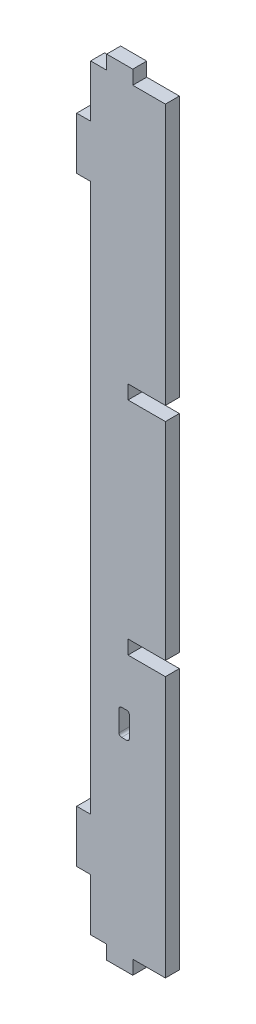
SolidWorks part; units mm, degrees
ref_plane "Front Plane" through (0, 0, 0) normal (0, 0, 1) x (1, 0, 0)
ref_plane "Top Plane" through (0, 0, 0) normal (0, 1, 0) x (1, 0, 0)
ref_plane "Right Plane" through (0, 0, 0) normal (1, 0, 0) x (0, 0, -1)
sketch "Model" plane through (0, 0, 0) normal (0, 0, 1) x (1, 0, 0)
  line L0 (20.1976, 77.8114) -> (20.1976, 85.8114)
  line L1 (19.1976, 86.8114) -> (17.1976, 86.8114)
  line L2 (16.1976, 85.8114) -> (16.1976, 77.8114)
  line L3 (17.1976, 76.8114) -> (19.1976, 76.8114)
  line L4 (0, 25.35) -> (5.35, 25.35)
  line L5 (0, 45.35) -> (0, 25.35)
  line L6 (5.35, 45.35) -> (0, 45.35)
  line L7 (5.35, 255.35) -> (5.35, 45.35)
  line L8 (0, 255.35) -> (5.35, 255.35)
  line L9 (0, 275.35) -> (0, 255.35)
  line L10 (5.35, 275.35) -> (0, 275.35)
  line L11 (5.35, 295.35) -> (5.35, 275.35)
  line L12 (11.5, 295.35) -> (5.35, 295.35)
  line L13 (11.5, 300.7) -> (11.5, 295.35)
  line L14 (21.5, 300.7) -> (11.5, 300.7)
  line L15 (21.5, 295.35) -> (21.5, 300.7)
  line L16 (34, 295.35) -> (21.5, 295.35)
  line L17 (34, 195.35) -> (34, 295.35)
  line L18 (19.675, 195.35) -> (34, 195.35)
  line L19 (19.675, 190) -> (19.675, 195.35)
  line L20 (34, 190) -> (19.675, 190)
  line L21 (34, 110.7) -> (34, 190)
  line L22 (19.675, 110.7) -> (34, 110.7)
  line L23 (19.675, 105.35) -> (19.675, 110.7)
  line L24 (34, 105.35) -> (19.675, 105.35)
  line L25 (34, 5.35) -> (34, 105.35)
  line L26 (21.5, 5.35) -> (34, 5.35)
  line L27 (21.5, 0) -> (21.5, 5.35)
  line L28 (11.5, 0) -> (21.5, 0)
  line L29 (11.5, 5.35) -> (11.5, 0)
  line L30 (5.35, 5.35) -> (11.5, 5.35)
  line L31 (5.35, 25.35) -> (5.35, 5.35)
  arc A0 (19.1976, 76.8114) -> (20.1976, 77.8114) centre (19.1976, 77.8114) ccw
  arc A1 (20.1976, 85.8114) -> (19.1976, 86.8114) centre (19.1976, 85.8114) ccw
  arc A2 (17.1976, 86.8114) -> (16.1976, 85.8114) centre (17.1976, 85.8114) ccw
  arc A3 (16.1976, 77.8114) -> (17.1976, 76.8114) centre (17.1976, 77.8114) ccw
extrude "Boss-Extrude1" add sketch "Model" along normal blind 5.35
